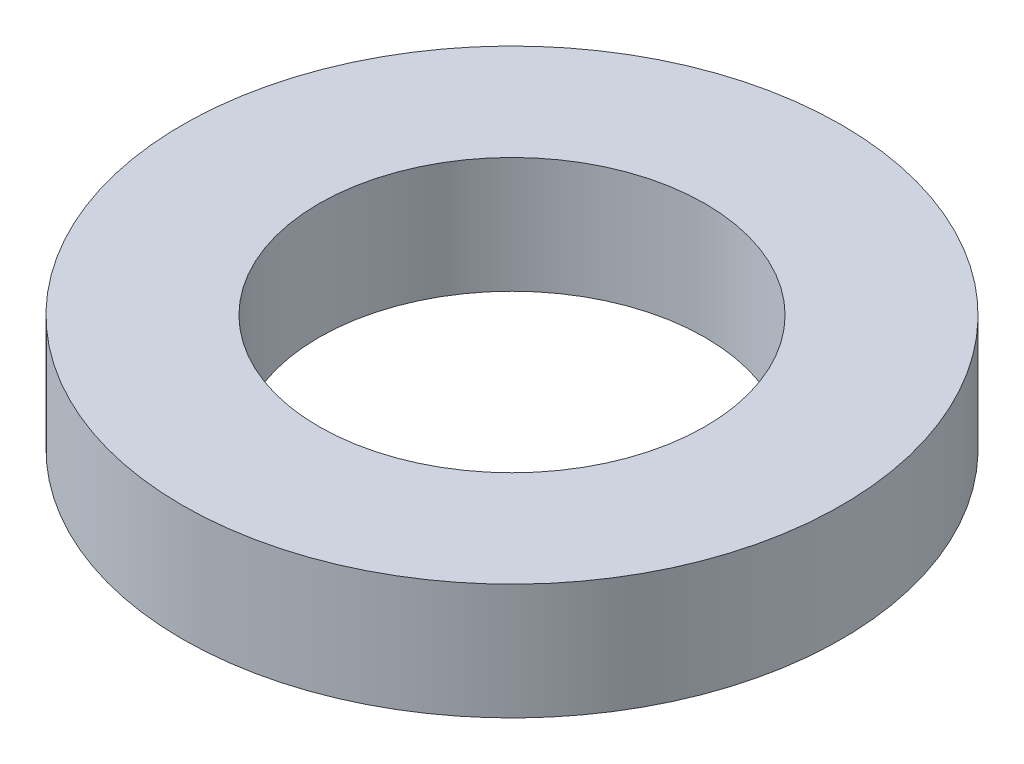
SolidWorks part; units mm, degrees
ref_plane "Front Plane" through (0, 0, 0) normal (0, 0, 1) x (1, 0, 0)
ref_plane "Top Plane" through (0, 0, 0) normal (0, 1, 0) x (1, 0, 0)
ref_plane "Right Plane" through (0, 0, 0) normal (1, 0, 0) x (0, 0, -1)
sketch "Sketch1" plane through (0, 0, 0) normal (0, 1, 0) x (1, 0, 0)
  circle A0 centre (0, 0) radius 12.8
  circle A1 centre (0, 0) radius 7.5
extrude "Boss-Extrude1" add sketch "Sketch1" along normal blind 4.5
